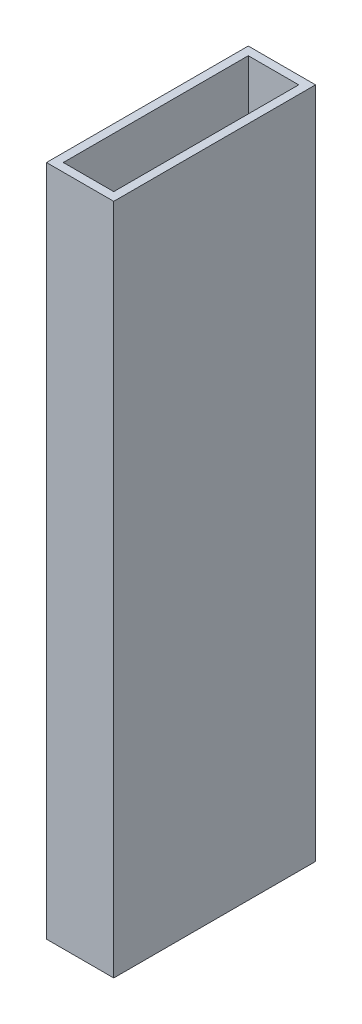
SolidWorks part; units mm, degrees
ref_plane "Front" through (0, 0, 0) normal (0, 0, 1) x (1, 0, 0)
ref_plane "Top" through (0, 0, 0) normal (0, 1, 0) x (1, 0, 0)
ref_plane "Right" through (0, 0, 0) normal (1, 0, 0) x (0, 0, -1)
sketch "Sketch1" plane through (0, 0, 0) normal (0, 1, 0) x (1, 0, 0)
  line L0 (0, 76.2) -> (0, 73.025)
  line L1 (0, 0) -> (25.4, 0)
  line L2 (0, 0) -> (0, 76.2)
  line L3 (0, 76.2) -> (25.4, 76.2)
  line L4 (25.4, 0) -> (25.4, 76.2)
  line L5 (0, 73.025) -> (25.4, 73.025)
  line L6 (25.4, 0) -> (25.4, 3.175)
  line L7 (25.4, 3.175) -> (0, 3.175)
  line L8 (0, 3.175) -> (3.175, 3.175)
  line L9 (25.4, 3.175) -> (22.225, 3.175)
  line L10 (22.225, 3.175) -> (22.225, 73.025)
  line L11 (3.175, 3.175) -> (3.175, 73.025)
  dimension "D1" = 25.4
  dimension "D2" = 76.2
  dimension "D3" = 3.175
  dimension "D4" = 3.175
  dimension "D5" = 3.175
  dimension "D6" = 3.175
extrude "Boss-Extrude1" add sketch "Sketch1" along normal blind 254 contours L7 L11 L5 L2 | L4 L7 L2 L1 | L10 L7 L4 L5 | L0 L5 L4 L3
